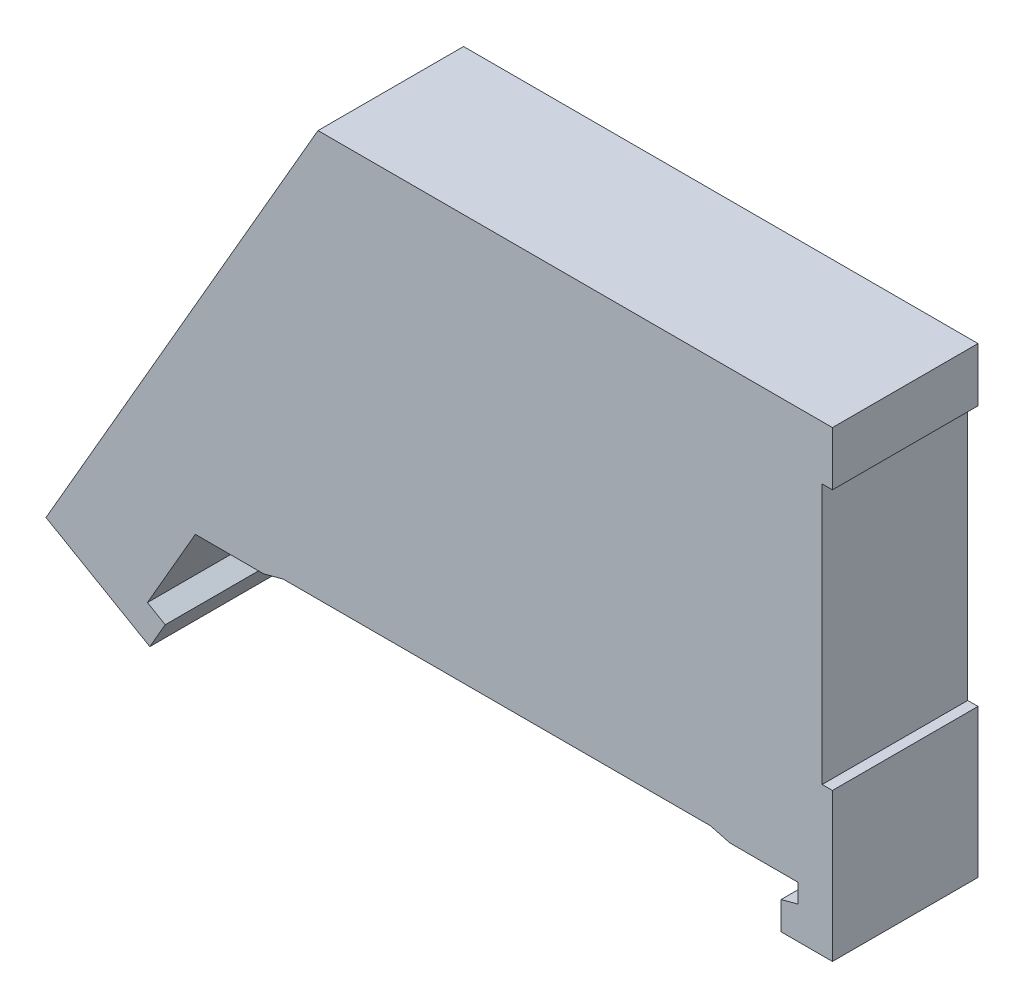
SolidWorks part; units mm, degrees
material "PBT Uniwersalny"
ref_plane "Płaszczyzna przednia" through (0, 0, 0) normal (0, 0, 1) x (1, 0, 0)
ref_plane "Płaszczyzna górna" through (0, 0, 0) normal (0, 1, 0) x (1, 0, 0)
ref_plane "Płaszczyzna prawa" through (0, 0, 0) normal (1, 0, 0) x (0, 0, -1)
ref_plane "Płaszczyzna1" through (0, 0, 0) normal (0, 0, -1) x (-1, 0, 0)
sketch "Szkic1" plane through (0, 0, 0) normal (0, 0, -1) x (-1, 0, 0)
  line L0 (-8.0804, 0.3) -> (16.8804, 0.3)
  line L1 (16.8804, 0.3) -> (18, 0)
  line L2 (18, 0) -> (22, 0)
  line L3 (22, 0) -> (24.8, -4.8497)
  line L4 (24.8, -4.8497) -> (23.7599, -5.4502)
  line L5 (23.7599, -5.4502) -> (24.6599, -7.0091)
  line L6 (24.6599, -7.0091) -> (30.7221, -3.5091)
  line L7 (30.7221, -3.5091) -> (14.8397, 24)
  line L8 (14.8397, 24) -> (-15.2, 24)
  line L9 (-15.2, 24) -> (-15.2, 20.85)
  line L10 (-15.2, 20.85) -> (-14.6, 20.85)
  line L11 (-14.6, 20.85) -> (-14.6, 5.65)
  line L12 (-14.6, 5.65) -> (-15.2, 5.65)
  line L13 (-15.2, 5.65) -> (-15.2, -3)
  line L14 (-15.2, -3) -> (-12.2, -3)
  line L15 (-12.2, -3) -> (-12.2, -1.3679)
  line L16 (-12.2, -1.3679) -> (-13.2, -1.1)
  line L17 (-13.2, -1.1) -> (-13.2, 0)
  line L18 (-13.2, 0) -> (-9.2, 0)
  line L19 (-9.2, 0) -> (-8.0804, 0.3)
extrude "Dodanie-wyciągnięcie1" add sketch "Szkic1" against normal blind 8.5
